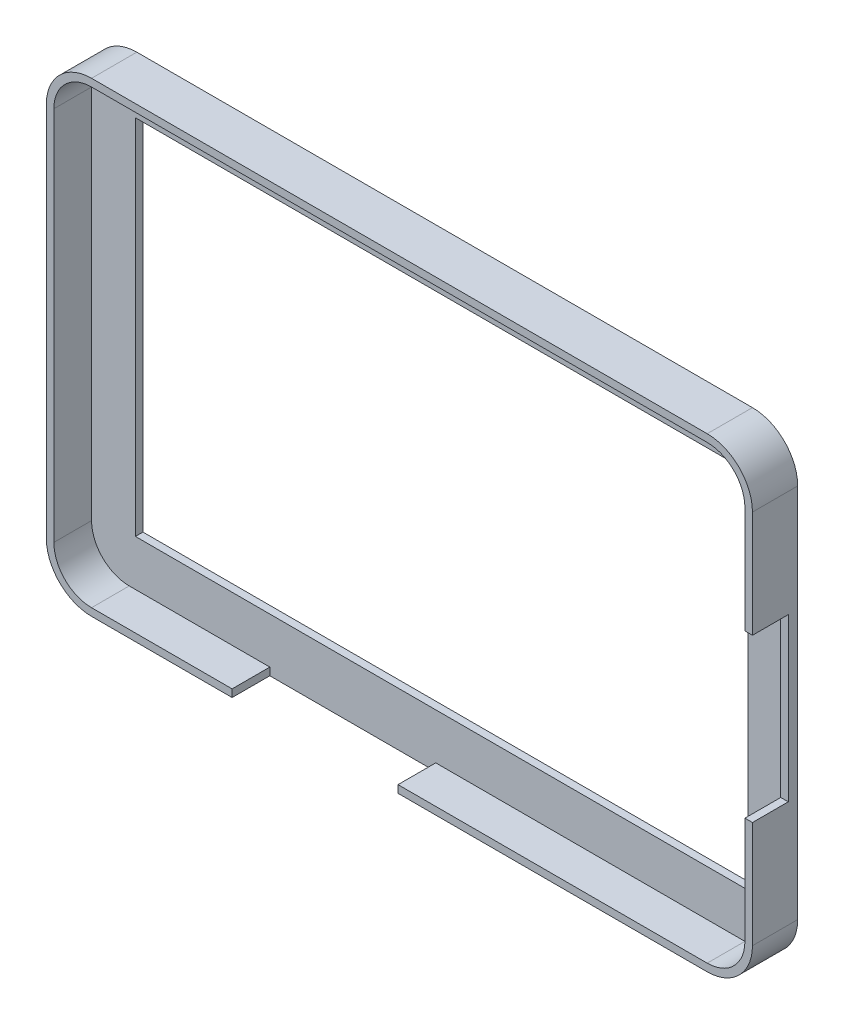
SolidWorks part; units mm, degrees
ref_plane "Ebene vorne" through (0, 0, 0) normal (1, 0, 0) x (0, 1, 0)
ref_plane "Ebene oben" through (0, 0, 0) normal (0, 0, 1) x (0, 1, 0)
ref_plane "Ebene rechts" through (0, 0, 0) normal (0, 1, 0) x (-1, 0, 0)
sketch "Skizze1" plane through (0, 0, 0) normal (0, 0, 1) x (0, 1, 0)
  line L0 (-30.9, -46.82) -> (30.9, -46.82)
  line L1 (-30.9, -46.82) -> (-30.9, 46.82)
  line L2 (-30.9, 46.82) -> (30.9, 46.82)
  line L3 (30.9, -46.82) -> (30.9, 46.82)
  line L4 (-30.9, -46.82) -> (30.9, 46.82) construction
  line L5 (-30.9, 46.82) -> (30.9, -46.82) construction
  point P0 (0, 0)
  point P5 (0, 0)
  dimension "D1" = 61.8
  dimension "D2" = 93.64
extrude "Aufsatz-Linear austragen1" add sketch "Skizze1" along normal blind 6
fillet "Verrundung1" radius 6 4 edges at (46.82, -30.9, 3) (-46.82, -30.9, 3) (-46.82, 30.9, 3) (46.82, 30.9, 3)
shell "Wandung1" thickness 1
sketch "Skizze2" plane through (46.82, 0, 0) normal (1, 0, 0) x (0, 1, 0)
  line L0 (-24.9, 6) -> (24.9, 6) construction
  line L1 (-10.75, 10.75) -> (10.75, 10.75)
  line L2 (-10.75, 10.75) -> (-10.75, 1.25)
  line L3 (-10.75, 1.25) -> (10.75, 1.25)
  line L4 (10.75, 10.75) -> (10.75, 1.25)
  line L5 (-10.75, 10.75) -> (10.75, 1.25) construction
  line L6 (-10.75, 1.25) -> (10.75, 10.75) construction
  point P0 (0, 6)
  dimension "D1" = 21.5
  dimension "D2" = 9.5
extrude "Schnitt-Linear austragen1" cut sketch "Skizze2" against normal blind 6
sketch "Skizze3" plane through (0, -30.9, 0) normal (0, -1, 0) x (1, 0, 0)
  line L0 (-40.82, 6) -> (40.82, 6) construction
  line L1 (-0.18, 6) -> (-22.18, 6)
  line L2 (-0.18, 6) -> (-0.18, 1)
  line L3 (-0.18, 1) -> (-22.18, 1)
  line L4 (-22.18, 6) -> (-22.18, 1)
  dimension "D1" = 22
  dimension "D2" = 5
  dimension "D3" = 41
extrude "Schnitt-Linear austragen2" cut sketch "Skizze3" against normal blind 6
sketch "Skizze4" plane through (0, 0, 0) normal (0, 0, -1) x (1, 0, 0)
  line L1 (-40.0035, 23.808) -> (41.2523, 23.808)
  line L2 (-40.0035, 23.808) -> (-40.0035, -24.277)
  line L3 (-40.0035, -24.277) -> (41.2523, -24.277)
  line L4 (41.2523, 23.808) -> (41.2523, -24.277)
extrude "Schnitt-Linear austragen3" cut sketch "Skizze4" against normal blind 6
